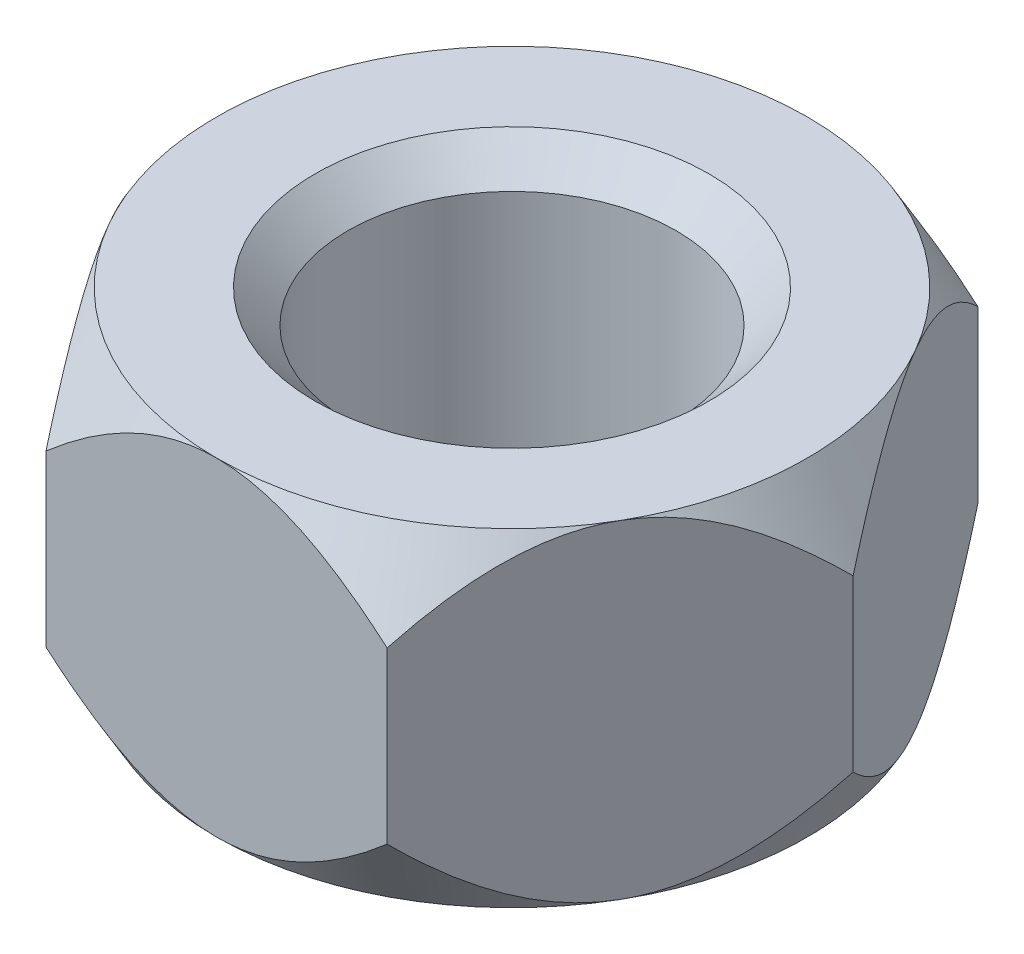
SolidWorks part; units mm, degrees
ref_plane "前视基准面" through (0, 0, 0) normal (0, 0, 1) x (1, 0, 0)
ref_plane "上视基准面" through (0, 0, 0) normal (0, 1, 0) x (1, 0, 0)
ref_plane "右视基准面" through (0, 0, 0) normal (1, 0, 0) x (0, 0, -1)
sketch "草图1" plane through (0, 0, 0) normal (0, 1, 0) x (1, 0, 0)
  line L1 (2.5981, 4.5) -> (-2.5981, 4.5)
  line L2 (-2.5981, 4.5) -> (-5.1962, 0)
  line L3 (-5.1962, 0) -> (-2.5981, -4.5)
  line L4 (-2.5981, -4.5) -> (2.5981, -4.5)
  line L5 (2.5981, -4.5) -> (5.1962, 0)
  line L6 (5.1962, 0) -> (2.5981, 4.5)
  circle A0 centre (0, 0) radius 4.5 construction
  dimension "D1" = 9
extrude "凸台-拉伸1" add sketch "草图1" along normal blind 5
sketch "草图2" plane through (0, 5, 0) normal (0, 1, 0) x (1, 0, 0)
  circle A0 centre (0, 0) radius 2.5
  dimension "D1" = 5
extrude "切除-拉伸1" cut sketch "草图2" against normal blind 5
cosmetic thread "装饰螺纹线1" parameters "D1"=5, "D2"=6
sketch "草图3" plane through (0, 5, 0) normal (0, 1, 0) x (1, 0, 0)
  circle A0 centre (0, 0) radius 4.5
  dimension "D1" = 9
extrude "切除-拉伸2" cut sketch "草图3" against normal blind 5 draft 30 flip side to cut
sketch "草图4" plane through (0, 0, 0) normal (0, -1, 0) x (1, 0, 0)
  circle A0 centre (0, 0) radius 4.5
extrude "切除-拉伸3" cut sketch "草图4" against normal blind 5 draft 30 flip side to cut
chamfer "倒角1" distance 0.5 angle 45 1 edges at (0, 5, 2.5)
chamfer "倒角2" distance 0.5 angle 45 1 edges at (0, 0, 2.5)
